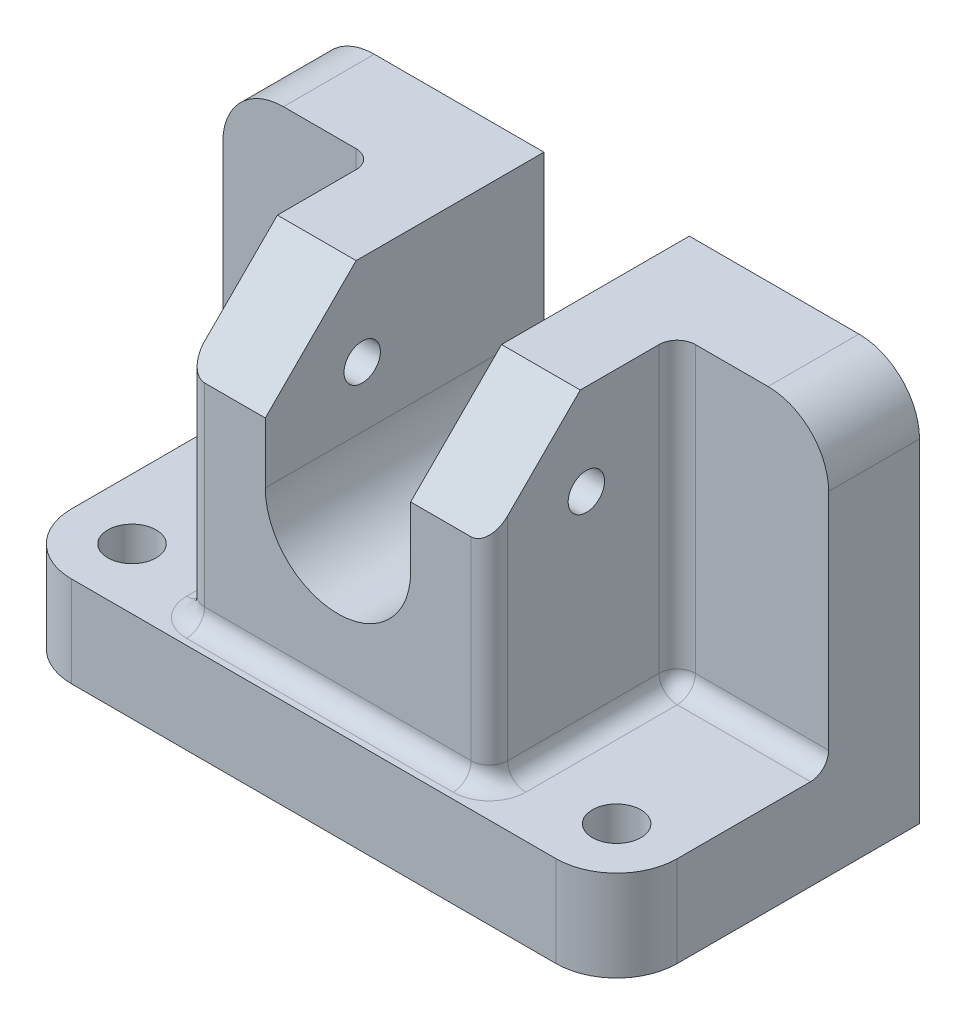
SolidWorks part; units mm, degrees
material "Aluminum Bronze"
ref_plane "Front" through (0, 0, 0) normal (0, 0, 1) x (1, 0, 0)
ref_plane "Top" through (0, 0, 0) normal (0, 1, 0) x (1, 0, 0)
ref_plane "Right" through (0, 0, 0) normal (1, 0, 0) x (0, 0, -1)
sketch "Sketch1" plane through (0, 0, 0) normal (0, 0, 1) x (1, 0, 0)
  line L1 (-50, 0) -> (50, 0)
  line L2 (-50, 0) -> (-50, 65)
  line L3 (-50, 65) -> (50, 65)
  line L4 (50, 0) -> (50, 65)
  dimension "D1" = 100
  dimension "D2" = 65
extrude "Base-Extrude" add sketch "Sketch1" along normal blind 50
sketch "Sketch2" plane through (50, 0, 0) normal (1, 0, 0) x (0, 0, -1)
  line L0 (-50, 0) -> (0, 0) construction
  line L1 (-50, 65) -> (-15, 65)
  line L2 (-50, 65) -> (-50, 15)
  line L3 (-50, 15) -> (-15, 15)
  line L4 (-15, 65) -> (-15, 15)
  line L5 (0, 0) -> (0, 65) construction
  dimension "D1" = 15
  dimension "D2" = 15
extrude "Cut-Extrude1" cut sketch "Sketch2" against normal through all
sketch "Sketch3" plane through (0, 15, 0) normal (0, 1, 0) x (-1, 0, 0)
  line L0 (50, 15) -> (-50, 15) construction
  line L1 (25, 15) -> (-25, 15)
  line L2 (25, 15) -> (25, 46)
  line L3 (25, 46) -> (-25, 46)
  line L4 (-25, 15) -> (-25, 46)
  line L5 (-50, 0) -> (50, 0) construction
  line L7 (0, 46) -> (0, 0) construction
  dimension "D1" = 46
  dimension "D2" = 50
extrude "Boss-Extrude1" add sketch "Sketch3" along normal up to surface (50 mm away)
sketch "Sketch4" plane through (0, 0, 46) normal (0, 0, 1) x (1, 0, 0)
  line L0 (-12, 65) -> (-12, 40)
  line L1 (25, 65) -> (-25, 65) construction
  line L2 (12, 40) -> (12, 65)
  line L3 (12, 65) -> (-12, 65)
  arc A0 (-12, 40) -> (12, 40) centre (0, 40) ccw
  dimension "D1" = 12
  dimension "D2" = 25
extrude "Cut-Extrude2" cut sketch "Sketch4" against normal through all
chamfer "Chamfer1" distance 15 angle 45 2 edges at (18.5, 65, 46) (-18.5, 65, 46)
fillet "Fillet1" radius 10 4 edges at (50, 7.5, 50) (-50, 7.5, 50) (-50, 65, 7.5) (50, 65, 7.5)
fillet "Fillet2" radius 3 2 edges at (25, 40, 15) (-25, 40, 15)
fillet "Fillet3" radius 3 2 edges at (-25, 32.5, 46) (25, 32.5, 46)
fillet "Fillet4" radius 3 9 edges at (39, 15, 15) (25.8787, 15, 15.8787) (25, 15, 30.5) (24.1213, 15, 45.1213) (0, 15, 46) (-24.1213, 15, 45.1213) (-25, 15, 30.5) (-25.8787, 15, 15.8787) (-39, 15, 15)
hole_wizard "Ø8.0 (8) Diameter Hole1" positions "Sketch5" profile "Sketch6" hole size "Ø8.0" standard "ANSI Metric" end condition through all
sketch "Sketch5" plane through (0, 15, 0) normal (0, 1, 0) x (1, 0, 0)
  point P0 (40, -40)
  point P3 (-40, -40)
sketch "Sketch6" plane through (40, 15, 40) normal (1, 0, 0) x (0, 0, 1)
  line L0 (0, 0) -> (0, 15)
  line L1 (0, 15) -> (4, 15)
  line L2 (4, 15) -> (4, 0)
  line L5 (4, 0) -> (0, 0)
  line L11 (0, -6.35) -> (0, 107.95) construction
  dimension "Thru Hole Dia." = 8
  dimension "Thru Hole Depth" = 15
hole_wizard "Ø6.0 (6) Diameter Hole1" positions "Sketch7" profile "Sketch8" hole size "Ø6.0" standard "ANSI Metric" end condition through all
sketch "Sketch7" plane through (25, 0, 0) normal (1, 0, 0) x (0, 0, -1)
  line L0 (-40, 0) -> (0, 0) construction
  line L1 (0, 0) -> (0, 55) construction
  point P0 (-30, 50)
  dimension "D1" = 50
  dimension "D2" = 30
sketch "Sketch8" plane through (25, 50, 30) normal (0, 1, 0) x (0, 0, -1)
  line L0 (0, 0) -> (0, 75)
  line L1 (0, 75) -> (3, 75)
  line L2 (3, 75) -> (3, 0)
  line L5 (3, 0) -> (0, 0)
  line L11 (0, -6.35) -> (0, 107.95) construction
  dimension "Thru Hole Dia." = 6
  dimension "Thru Hole Depth" = 75
